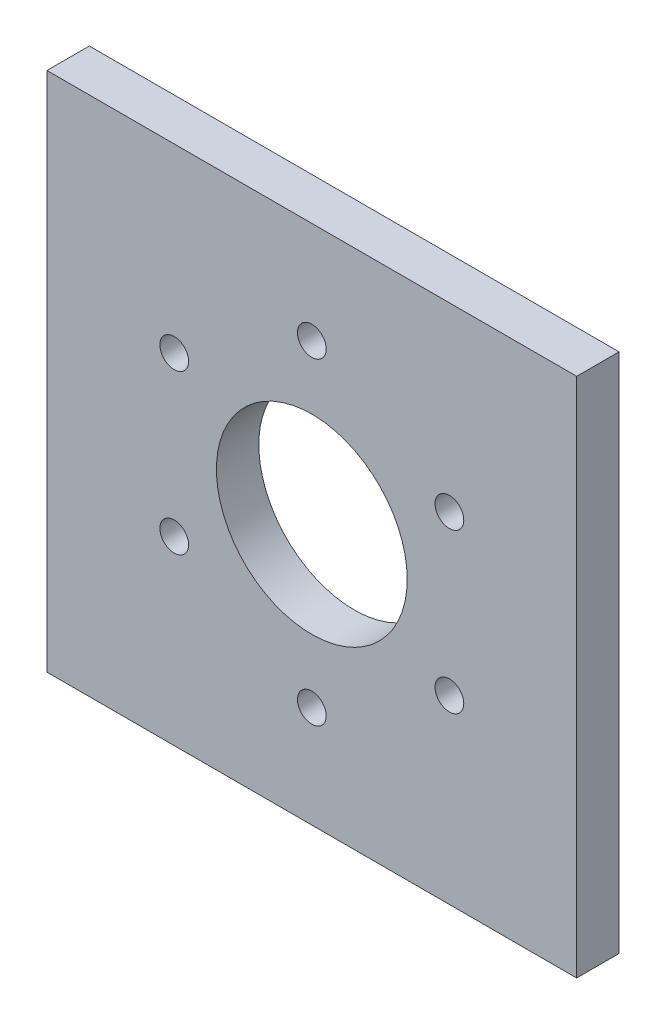
SolidWorks part; units mm, degrees
ref_plane "Front Plane" through (0, 0, 0) normal (0, 0, 1) x (1, 0, 0)
ref_plane "Top Plane" through (0, 0, 0) normal (0, 1, 0) x (1, 0, 0)
ref_plane "Right Plane" through (0, 0, 0) normal (1, 0, 0) x (0, 0, -1)
sketch "Sketch1" plane through (0, 0, 0) normal (0, 0, 1) x (1, 0, 0)
  line L5 (0, 39.0525) -> (39.7, 39.0525)
  line L8 (39.7, 39.0525) -> (39.7, 0)
  line L9 (0, -39.0525) -> (39.7, -39.0525)
  line L12 (39.7, -39.0525) -> (39.7, 0)
  line L14 (-39.7, 0) -> (-39.7, 39.0525)
  line L15 (-39.7, 39.0525) -> (0, 39.0525)
  line L18 (-39.7, 0) -> (-39.7, -39.0525)
  line L19 (-39.7, -39.0525) -> (0, -39.0525)
  arc A4 (2.1526, 23.8125) -> (-2.1526, 23.8125) centre (0, 23.8125) ccw
  arc A5 (-2.1526, 23.8125) -> (2.1526, 23.8125) centre (0, 23.8125) ccw
  arc A6 (-14.3, 0) -> (14.3, 0) centre (0, 0) ccw
  arc A7 (14.3, 0) -> (-14.3, 0) centre (0, 0) ccw
  arc A10 (-22.7749, 11.9063) -> (-18.4696, 11.9063) centre (-20.6222, 11.9063) ccw
  arc A11 (-18.4696, 11.9063) -> (-22.7749, 11.9063) centre (-20.6222, 11.9063) ccw
  arc A14 (-22.7749, -11.9062) -> (-18.4696, -11.9062) centre (-20.6222, -11.9062) ccw
  arc A15 (-18.4696, -11.9062) -> (-22.7749, -11.9062) centre (-20.6222, -11.9062) ccw
  arc A18 (-2.1526, -23.8125) -> (2.1526, -23.8125) centre (0, -23.8125) ccw
  arc A19 (2.1526, -23.8125) -> (-2.1526, -23.8125) centre (0, -23.8125) ccw
  arc A22 (18.4696, 11.9062) -> (22.7749, 11.9062) centre (20.6222, 11.9062) ccw
  arc A23 (22.7749, 11.9062) -> (18.4696, 11.9062) centre (20.6222, 11.9062) ccw
  arc A26 (18.4696, -11.9062) -> (22.7749, -11.9062) centre (20.6222, -11.9062) ccw
  arc A27 (22.7749, -11.9062) -> (18.4696, -11.9062) centre (20.6222, -11.9062) ccw
  dimension "D1" = 15.24
  dimension "D2" = 15.24
  dimension "D3" = 25.4
  dimension "D4" = 25.4
extrude "Boss-Extrude1" add sketch "Sketch1" along normal blind 6.35
